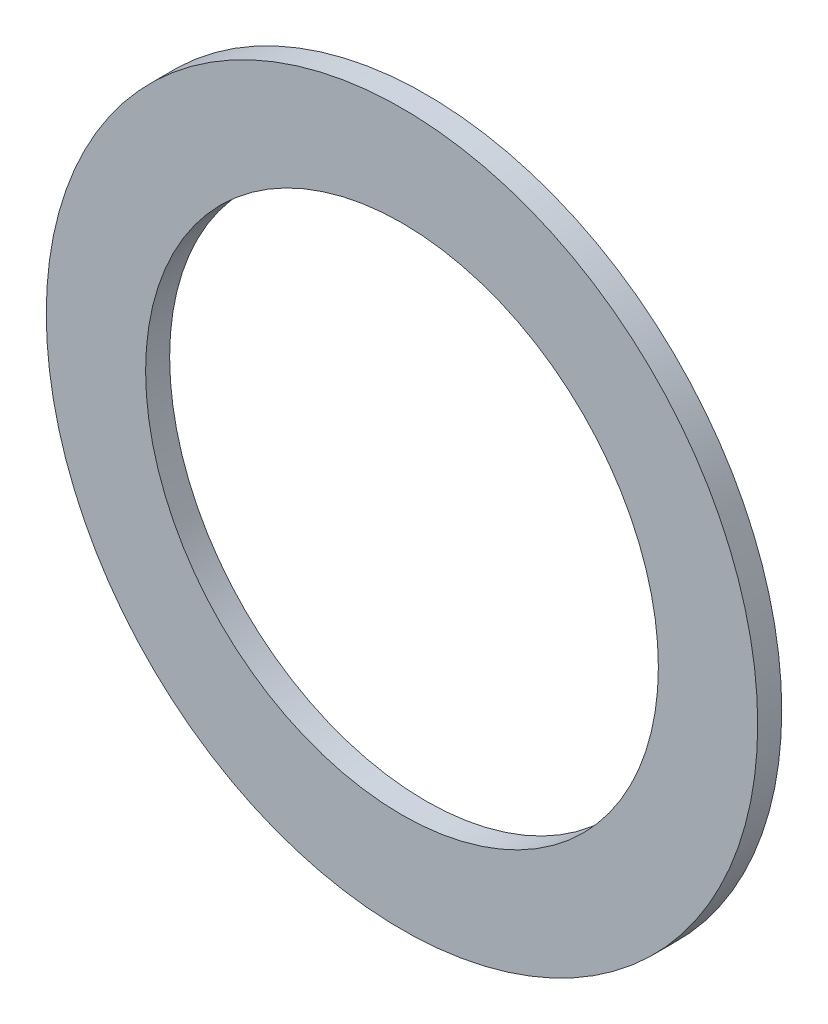
SolidWorks part; units mm, degrees
ref_plane "Спереди" through (0, 0, 0) normal (0, 0, 1) x (1, 0, 0)
ref_plane "Сверху" through (0, 0, 0) normal (0, 1, 0) x (1, 0, 0)
ref_plane "Справа" through (0, 0, 0) normal (1, 0, 0) x (0, 0, -1)
sketch "Эскиз1" plane through (0, 0, 0) normal (0, 0, 1) x (1, 0, 0)
  circle A0 centre (0, 0) radius 22.2
  circle A1 centre (0, 0) radius 16
extrude "Stack_washer" add sketch "Эскиз1" along normal blind 1.5 from offset 20
